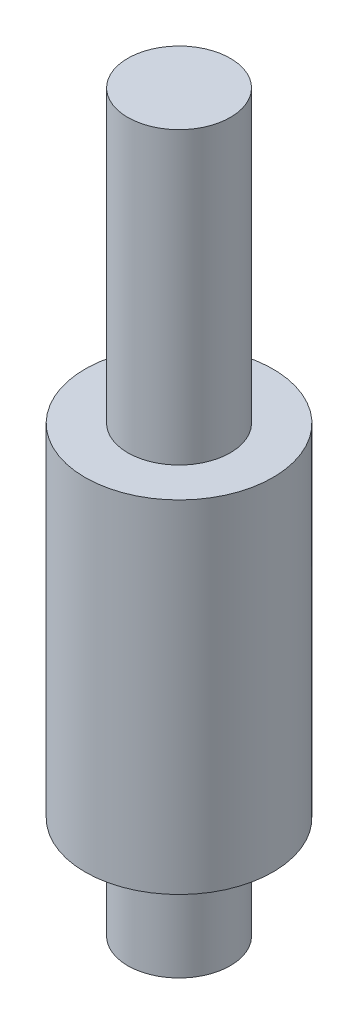
SolidWorks part; units mm, degrees
ref_plane "Front Plane" through (0, 0, 0) normal (0, 0, 1) x (1, 0, 0)
ref_plane "Top Plane" through (0, 0, 0) normal (0, 1, 0) x (1, 0, 0)
ref_plane "Right Plane" through (0, 0, 0) normal (1, 0, 0) x (0, 0, -1)
sketch "Sketch1" plane through (0, 0, 0) normal (0, 1, 0) x (1, 0, 0)
  circle A0 centre (0, 0) radius 3
  dimension "D1" = 6
extrude "Boss-Extrude1" add sketch "Sketch1" along normal blind 6
cosmetic thread "Cosmetic Thread2" parameters "D1"=5, "D2"=5
sketch "Sketch2" plane through (0, 6, 0) normal (0, 1, 0) x (1, 0, 0)
  circle A0 centre (0, 0) radius 5.5
  dimension "D1" = 11
extrude "Boss-Extrude2" add sketch "Sketch2" along normal blind 20
sketch "Sketch3" plane through (0, 26, 0) normal (0, 1, 0) x (1, 0, 0)
  circle A0 centre (0, 0) radius 3
  dimension "D1" = 6
extrude "Boss-Extrude3" add sketch "Sketch3" along normal blind 17
cosmetic thread "Cosmetic Thread1" parameters "D1"=12, "D2"=5
